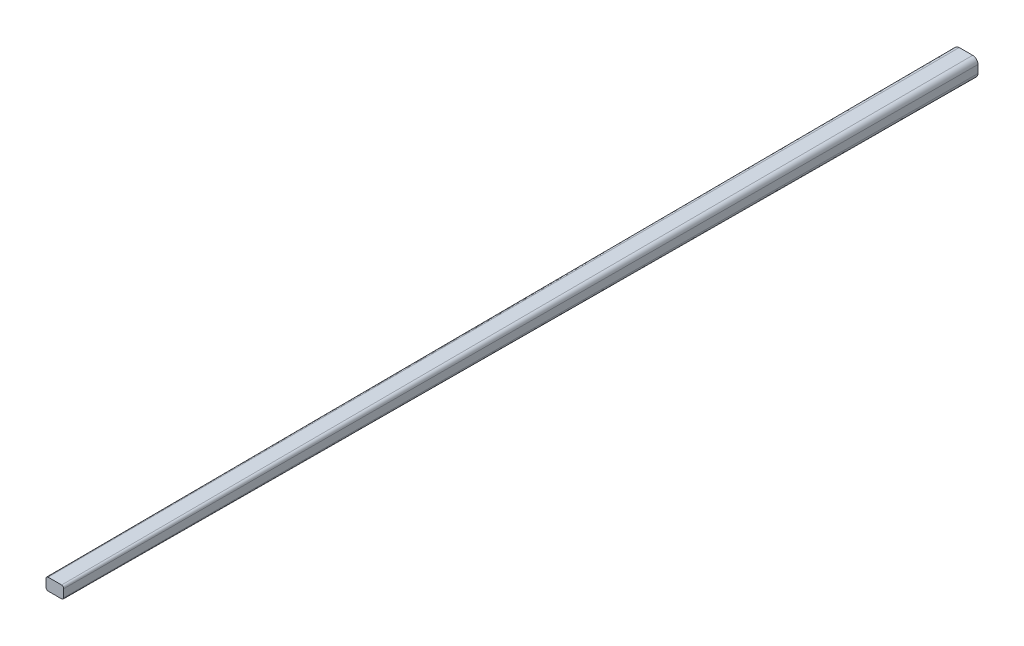
SolidWorks part; units mm, degrees
ref_plane "Front Plane" through (0, 0, 0) normal (0, 0, 1) x (1, 0, 0)
ref_plane "Top Plane" through (0, 0, 0) normal (0, 1, 0) x (1, 0, 0)
ref_plane "Right Plane" through (0, 0, 0) normal (1, 0, 0) x (0, 0, -1)
sketch "Sketch1" plane through (0, 0, 0) normal (0, 0, 1) x (1, 0, 0)
  line L12 (-805.9594, -1279.4372) -> (-805.9594, -1277.2372)
  line L13 (-807.4594, -1275.7372) -> (-811.2594, -1275.7372)
  line L14 (-812.7594, -1277.2372) -> (-812.7594, -1279.4372)
  line L15 (-811.2594, -1280.9372) -> (-807.4594, -1280.9372)
  line L16 (-814.3601, -1282.4167) -> (-812.0817, -1282.4167)
  line L17 (-814.3255, -1272.4167) -> (-814.3601, -1282.4167)
  line L18 (-804.3594, -1272.4167) -> (-814.3255, -1272.4167)
  line L19 (-804.3594, -1282.4167) -> (-804.3594, -1272.4167)
  line L20 (-806.6326, -1282.4167) -> (-804.3594, -1282.4167)
  line L21 (-809.3669, -1281.7374) -> (-809.3669, -1276.3374)
  line L22 (-805.8658, -1279.0374) -> (-812.8682, -1279.0374)
  line L23 (-812.3945, -1276.8062) -> (-806.3243, -1276.8062)
  arc A16 (-805.9594, -1277.2372) -> (-807.4594, -1275.7372) centre (-807.4594, -1277.2372) ccw
  arc A17 (-811.2594, -1275.7372) -> (-812.7594, -1277.2372) centre (-811.2594, -1277.2372) ccw
  arc A18 (-812.7594, -1279.4372) -> (-812.3945, -1281.2687) centre (-807.9807, -1279.4372) ccw
  arc A19 (-807.4594, -1280.9372) -> (-805.9594, -1279.4372) centre (-807.4594, -1279.4372) ccw
  arc A20 (-812.7594, -1279.4372) -> (-811.2594, -1280.9372) centre (-811.2594, -1279.4372) ccw
  arc A21 (-806.3303, -1281.2823) -> (-805.9594, -1279.4372) centre (-810.7349, -1279.4372) ccw
  arc A22 (-812.3945, -1281.2687) -> (-811.9269, -1282.1016) centre (-807.7046, -1279.1835) ccw
  arc A23 (-812.0817, -1282.4167) -> (-811.9269, -1282.1016) centre (-812.084, -1282.22) ccw
  arc A24 (-806.7947, -1282.0996) -> (-806.6326, -1282.4167) centre (-806.6325, -1282.2167) ccw
  arc A25 (-806.7947, -1282.0996) -> (-806.3303, -1281.2823) centre (-810.3068, -1279.5633) ccw
  arc A26 (-806.3303, -1281.2823) -> (-806.3243, -1276.8062) centre (-811.5236, -1279.0373) ccw
  arc A27 (-806.3243, -1276.8062) -> (-807.7895, -1275.0211) centre (-810.1384, -1278.4429) ccw
  arc A28 (-807.7895, -1275.0211) -> (-810.9293, -1275.0211) centre (-809.3594, -1277.3258) ccw
  arc A29 (-810.9293, -1275.0211) -> (-812.3945, -1276.8062) centre (-808.6213, -1278.4094) ccw
  arc A30 (-812.3945, -1276.8062) -> (-812.3945, -1281.2687) centre (-807.3762, -1279.0374) ccw
  arc A31 (-806.3243, -1276.8062) -> (-812.3945, -1276.8062) centre (-809.3594, -1286.3981) ccw
  point P42 (0, 0)
extrude "Boss-Extrude1" add sketch "Sketch1" along normal blind 257 draft 0.2 contours A30 A29 A17 L14 | A31 A27 A16 L13 A17 A29 | A27 A26 L12 A16 | L23 A31 L21 | L21 A31 L23 | L23 A30 L14 L22 L21 | L12 A26 L23 L21 L22 | L15 A19 L12 L22 L21 | L14 A20 L15 L21 L22
ref_plane "Plane1" through (0, 0, 367) normal (0, 0, 1) x (1, 0, 0)
